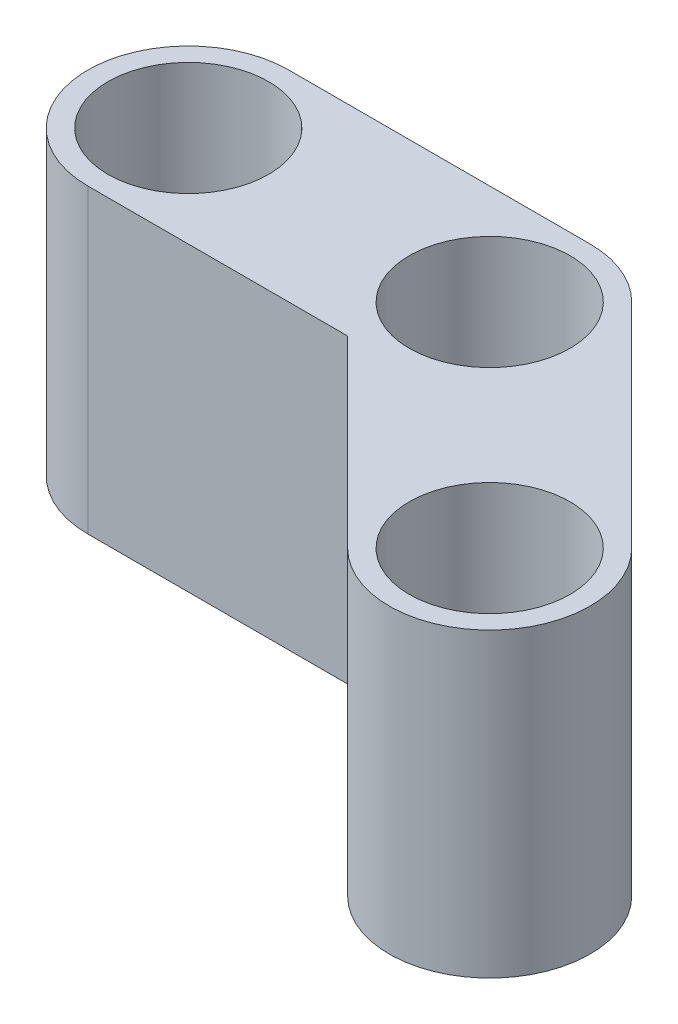
SolidWorks part; units mm, degrees
ref_plane "Front Plane" through (0, 0, 0) normal (0, 0, 1) x (1, 0, 0)
ref_plane "Top Plane" through (0, 0, 0) normal (0, 1, 0) x (1, 0, 0)
ref_plane "Right Plane" through (0, 0, 0) normal (1, 0, 0) x (0, 0, -1)
sketch "Sketch1" plane through (0, 0, 0) normal (0, 1, 0) x (1, 0, 0)
  line L0 (-12.5827, 26.3544) -> (-11.0827, 26.3544) construction
  line L1 (-12.5827, 26.8544) -> (-11.0827, 26.8544)
  line L2 (-12.5827, 25.8544) -> (-11.0827, 25.8544)
  line L4 (-11.0827, 26.3544) -> (-10.0221, 25.2938) construction
  line L5 (-10.7292, 26.708) -> (-9.6685, 25.6473)
  line L6 (-11.4363, 26.0009) -> (-10.3756, 24.9402)
  arc A0 (-12.5827, 26.8544) -> (-12.5827, 25.8544) centre (-12.5827, 26.3544) ccw
  arc A1 (-11.0827, 25.8544) -> (-11.0827, 26.8544) centre (-11.0827, 26.3544) ccw
  arc A2 (-10.7292, 26.708) -> (-11.4363, 26.0009) centre (-11.0827, 26.3544) ccw
  arc A3 (-10.3756, 24.9402) -> (-9.6685, 25.6473) centre (-10.0221, 25.2938) ccw
  circle A4 centre (-12.5827, 26.3544) radius 0.4
  circle A5 centre (-11.0827, 26.3544) radius 0.4
  circle A6 centre (-10.0221, 25.2938) radius 0.4
  point P2 (-11.8327, 26.3544)
  point P9 (-10.5524, 25.8241)
extrude "Boss-Extrude1" add sketch "Sketch1" along normal blind 1.5 contours A1 A2 L6 L2 A5 | A2 L1 A0 L2 L6 A4 | L6 A3 L5 A1 L2 A6
